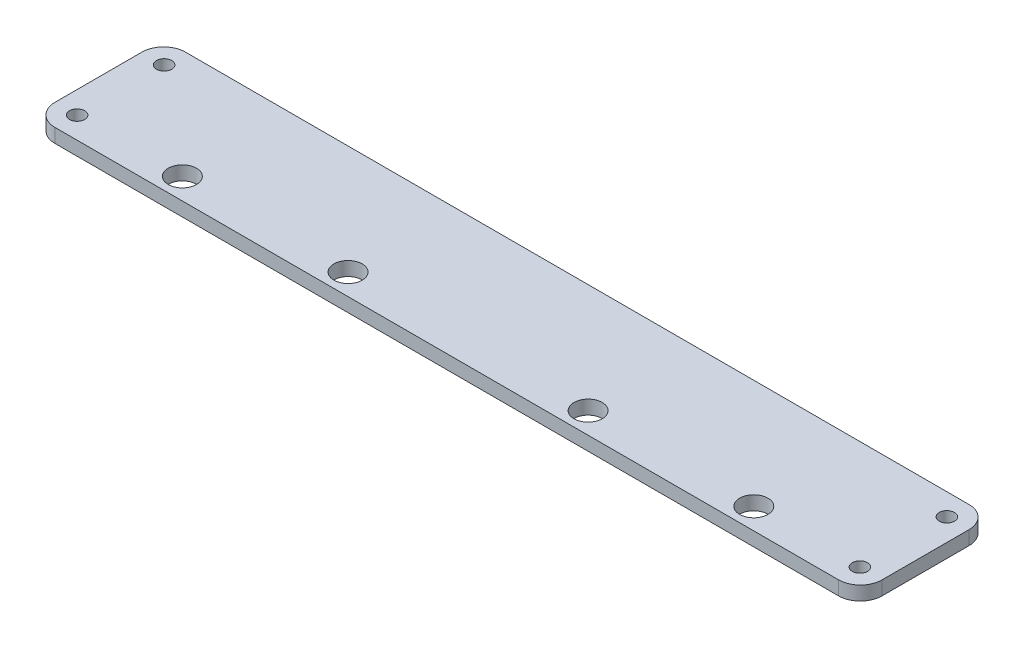
SolidWorks part; units mm, degrees
ref_plane "Front Plane" through (0, 0, 0) normal (0, 0, 1) x (1, 0, 0)
ref_plane "Top Plane" through (0, 0, 0) normal (0, 1, 0) x (1, 0, 0)
ref_plane "Right Plane" through (0, 0, 0) normal (1, 0, 0) x (0, 0, -1)
sketch "Sketch1" plane through (0, 0, 0) normal (0, 1, 0) x (1, 0, 0)
  line L1 (-95.1, -15) -> (95.1, -15)
  line L2 (-95.1, -15) -> (-95.1, 15)
  line L3 (-95.1, 15) -> (95.1, 15)
  line L4 (95.1, -15) -> (95.1, 15)
  line L5 (-95.1, -15) -> (95.1, 15) construction
  line L6 (-95.1, 15) -> (95.1, -15) construction
  point P0 (0, 0)
  dimension "D1" = 190.2
  dimension "D2" = 30
extrude "Boss-Extrude1" add sketch "Sketch1" along normal blind 3.2
sketch "Sketch2" plane through (0, 3.2, 0) normal (0, 1, 0) x (1, 0, 0)
  line L1 (-90, -10) -> (90, -10) construction
  line L2 (-90, -10) -> (-90, 10) construction
  line L3 (-90, 10) -> (90, 10) construction
  line L4 (90, -10) -> (90, 10) construction
  line L5 (-90, -10) -> (90, 10) construction
  line L6 (-90, 10) -> (90, -10) construction
  circle A0 centre (-90, 10) radius 1.75
  circle A1 centre (-90, -10) radius 1.75
  circle A2 centre (90, 10) radius 1.75
  circle A3 centre (90, -10) radius 1.75
  point P0 (0, 0)
  dimension "D3" = 3.5
  dimension "D1" = 20
  dimension "D2" = 180
extrude "Cut-Extrude1" cut sketch "Sketch2" against normal through all
sketch "Sketch3" plane through (0, 3.2, 0) normal (0, 1, 0) x (1, 0, 0)
  line L0 (-95.1, -10.1) -> (95.1, -10.1) construction
  line L1 (-95.1, 15) -> (-95.1, -15) construction
  line L2 (95.1, -15) -> (95.1, 15) construction
  circle A0 centre (65.7, -10.1) radius 3.25
  circle A1 centre (27.6, -10.1) radius 3.25
  circle A2 centre (-27.6, -10.1) radius 3.25
  circle A3 centre (-65.7, -10.1) radius 3.25
  circle A4 centre (90, -10) radius 1.75 construction
  circle A5 centre (-90, -10) radius 1.75 construction
  dimension "D1" = 6.5
  dimension "D2" = 24.3
  dimension "D3" = 24.3
  dimension "D4" = 0.1
  dimension "D5" = 38.1
  dimension "D6" = 38.1
extrude "Cut-Extrude2" cut sketch "Sketch3" against normal through all
fillet "Fillet1" radius 5 4 edges at (95.1, 1.6, 15) (95.1, 1.6, -15) (-95.1, 1.6, 15) (-95.1, 1.6, -15)
